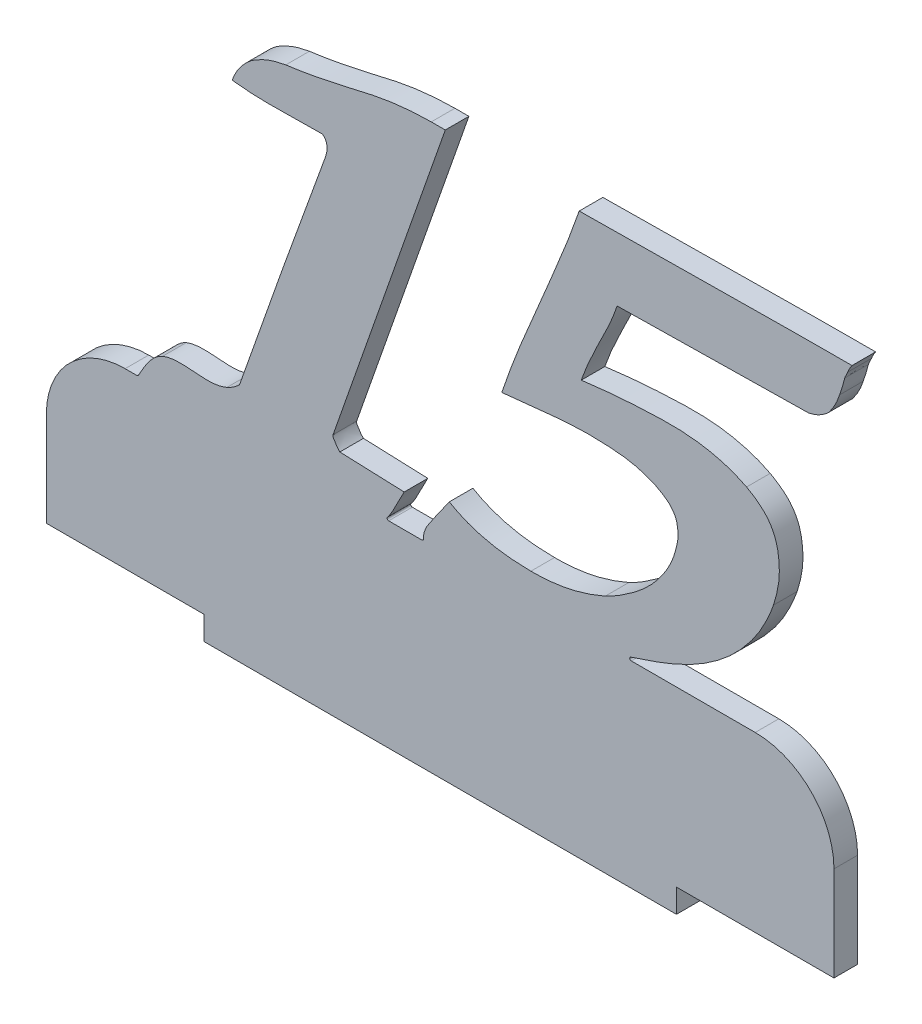
SolidWorks part; units mm, degrees
ref_plane "Front Plane" through (0, 0, 0) normal (0, 0, 1) x (1, 0, 0)
ref_plane "Top Plane" through (0, 0, 0) normal (0, 1, 0) x (1, 0, 0)
ref_plane "Right Plane" through (0, 0, 0) normal (1, 0, 0) x (0, 0, -1)
sketch "Sketch1" plane through (0, 0, 0) normal (0, 0, 1) x (1, 0, 0)
  line L0 (0, 20) -> (100, 20) construction
  line L1 (42.9468, 22) -> (47.8982, 22)
  line L2 (0, 22) -> (0, 0)
  line L3 (0, 0) -> (20, 0)
  line L4 (100, 22) -> (100, 0)
  line L5 (0, 22) -> (11.6163, 22)
  line L6 (90.1102, 22) -> (100, 22)
  line L7 (50.6494, 68.5735) -> (36.3999, 27.9363)
  line L8 (37.26, 26.4703) -> (45.4304, 26.1575)
  line L9 (96.8182, 60.5203) -> (72.4633, 60.1294)
  line L10 (72.918, 22) -> (90.1102, 22)
  line L11 (80, 0) -> (100, 0)
  line L13 (20, 0) -> (20, -3)
  line L14 (20, -3) -> (80, -3)
  line L15 (80, 0) -> (80, -3)
  spline S0 degree 3 poles (45.4304, 26.1575) (44.8355, 25.1443) (44.2903, 23.8221) (43.4345, 22.4246) (43.0957, 22.1163) (42.9468, 22) knots 0 0 0 0 0.504343 0.619768 0.70089 0.70089 0.70089 0.70089
  spline S1 degree 3 poles (11.6163, 22) (11.6951, 22.1343) (12.0206, 22.7022) (12.8266, 24.148) (13.8212, 25.3176) (14.7619, 25.7471) knots 0.170915 0.170915 0.170915 0.170915 0.248912 0.498933 1 1 1 1
  spline S2 degree 3 poles (14.7619, 25.7471) (16.1033, 26.2663) (18.8541, 25.9916) (21.6234, 25.8359) (22.9324, 26.4116) knots 0 0 0 0 0.501452 1 1 1 1
  spline S3 degree 2 poles (22.9324, 26.4116) (23.8139, 26.8022) (24.5157, 27.4672) knots 0 0 0 1 1 1
  spline S4 degree 3 poles (24.5157, 27.4672) (26.298, 32.5023) (29.823, 42.6251) (33.512, 52.6893) (35.3444, 57.7447) knots 0 0 0 0 0.498323 1 1 1 1
  spline S5 degree 3 poles (35.3444, 57.7447) (35.5276, 58.2423) (35.8228, 59.2088) (35.3702, 60.1202) (35.0121, 60.3249) knots 0 0 0 0 0.581397 1 1 1 1
  spline S6 degree 3 poles (35.0121, 60.3249) (33.0954, 60.3587) (29.2904, 60.1747) (25.4774, 60.2795) (23.597, 60.5203) knots 0 0 0 0 0.503015 1 1 1 1
  spline S7 degree 3 poles (23.597, 60.5203) (23.8289, 61.1875) (24.3132, 62.1365) (25.2312, 63.1972) (26.0045, 63.9197) (26.9524, 64.4734) (28.3794, 65.1561) (29.5715, 65.4709) (30.3992, 65.6024) knots 0 0 0 0 0.237267 0.352024 0.469659 0.590381 0.718477 1 1 1 1
  spline S8 degree 3 poles (30.3992, 65.6024) (33.5114, 66.0009) (37.3732, 66.8529) (41.995, 67.9327) (45.0749, 68.4152) (47.368, 68.5627) (48.8706, 68.5735) knots 0 0 0 0 0.501478 0.63281 0.759518 1 1 1 1
  spline S9 degree 3 poles (48.8706, 68.5735) (49.0791, 68.5735) (49.672, 68.5735) (50.2649, 68.5735) (50.6494, 68.5735) knots 0 0 0 0 0.351648 1 1 1 1
  spline S10 degree 3 poles (36.3999, 27.9363) (36.3468, 27.7365) (36.6784, 27.2268) (36.9561, 26.744) (37.26, 26.4703) knots 0 0 0 0 0.324502 1 1 1 1
  spline S11 degree 3 poles (92.3225, 37.1622) (91.7702, 35.6174) (90.7111, 33.3753) (88.7121, 30.7794) (87.021, 28.9699) (85.055, 27.3556) (82.8489, 25.8992) (80.3954, 24.6298) (77.7404, 23.5732) (75.2282, 22.704) (73.61, 22.2029) (72.918, 22) knots 0 0 0 0 0.120139 0.179294 0.238928 0.300824 0.364759 0.431861 0.502352 0.573447 0.626158 0.626158 0.626158 0.626158
  spline S13 degree 3 poles (47.8982, 22) (47.8835, 22.0952) (47.8462, 22.531) (48.0455, 23.3897) (48.6726, 24.4281) (49.4107, 25.443) (50.2199, 26.6356) (50.8129, 27.436) (51.1576, 27.9363) knots 0.184196 0.184196 0.184196 0.184196 0.218197 0.338419 0.488512 0.646372 0.784334 1 1 1 1
  spline S14 degree 3 poles (51.1576, 27.9363) (52.6052, 27.078) (56.0017, 25.802) (59.6114, 25.5069) (61.5172, 25.493) knots 0 0 0 0 0.467741 1 1 1 1
  spline S15 degree 3 poles (61.5172, 25.493) (63.1623, 25.4871) (66.4106, 25.7864) (69.5024, 26.8225) (70.9582, 27.4672) knots 0 0 0 0 0.508189 1 1 1 1
  spline S16 degree 3 poles (70.9582, 27.4672) (72.0392, 27.9891) (73.536, 28.8995) (75.3584, 30.2697) (76.5248, 31.3356) (77.5359, 32.4651) (78.6768, 34.0202) (79.3539, 35.2878) (79.6564, 36.1849) knots 0 0 0 0 0.285167 0.415664 0.541808 0.660346 0.775658 1 1 1 1
  spline S17 degree 3 poles (79.6564, 36.1849) (79.8495, 36.8136) (80.1343, 37.7234) (80.2311, 38.9298) (80.1396, 39.7105) (79.9861, 40.4244) (79.6496, 41.0468) (79.2204, 41.6046) (78.458, 42.2297) (77.3416, 42.8849) (75.8153, 43.4561) (74.1145, 43.904) (71.5713, 44.1672) (68.2052, 44.2958) (64.8201, 44.0361) (62.2151, 43.7366) (60.1238, 43.5188) (58.6885, 43.395) (57.8229, 43.2998) knots 0 0 0 0 0.071404 0.102518 0.130176 0.156356 0.180967 0.206089 0.232106 0.287157 0.345457 0.408083 0.477037 0.621747 0.772341 0.844017 0.905722 1 1 1 1
  spline S18 degree 3 poles (57.8229, 43.2998) (59.2314, 47.5145) (62.6881, 55.7326) (66.2091, 63.9226) (67.6548, 68.163) knots 0 0 0 0 0.497975 1 1 1 1
  spline S19 degree 3 poles (67.6548, 68.163) (73.4145, 68.2313) (84.9599, 68.3492) (96.5051, 68.5053) (102.2913, 68.4953) knots 0 0 0 0 0.498878 1 1 1 1
  spline S20 degree 2 poles (102.2913, 68.4953) (101.9657, 68.04) (101.7635, 67.518) knots 0 0 0 1 1 1
  spline S21 degree 3 poles (101.7635, 67.518) (101.6455, 67.2826) (101.5318, 67.0094) (101.369, 66.7207) (101.3726, 66.6579) knots 0 0 0 0 0.803037 1 1 1 1
  spline S22 degree 3 poles (101.3726, 66.6579) (101.2327, 66.1917) (101.0631, 65.4462) (100.8085, 64.7259) (100.708, 64.4687) knots 0 0 0 0 0.638073 1 1 1 1
  spline S23 degree 2 poles (100.708, 64.4687) (100.2746, 63.0654) (99.3788, 61.9081) knots 0 0 0 1 1 1
  spline S24 degree 2 poles (99.3788, 61.9081) (98.3081, 60.8421) (96.8182, 60.5203) knots 0 0 0 1 1 1
  spline S25 degree 3 poles (72.4633, 60.1294) (71.8819, 58.2941) (70.1425, 54.9138) (68.517, 51.479) (67.9089, 49.6916) knots 0 0 0 0 0.504223 1 1 1 1
  spline S26 degree 3 poles (67.9089, 49.6916) (69.5903, 49.9226) (72.1894, 50.1796) (75.7647, 50.4109) (78.6126, 50.5179) (81.4542, 50.4779) (84.9569, 49.9879) (87.4256, 49.2246) (88.9019, 48.4406) knots 0 0 0 0 0.238617 0.367155 0.503751 0.639403 0.766128 1 1 1 1
  spline S27 degree 3 poles (88.9019, 48.4406) (89.8888, 47.8925) (91.2987, 46.9181) (92.4454, 45.039) (92.8974, 43.5366) (93.0778, 41.9701) (93.0639, 39.8073) (92.6588, 38.2074) (92.3225, 37.1622) knots 0 0 0 0 0.263831 0.382077 0.502054 0.62342 0.745364 1 1 1 1
  dimension "D1" = 100
  dimension "D2" = 3
  dimension "D3" = 20
  dimension "D4" = 20
  dimension "D5" = 20
extrude "Boss-Extrude1" add sketch "Sketch1" along normal blind 3
fillet "Fillet1" radius 10 2 edges at (0, 22, 1.5) (100, 22, 1.5)
fillet "Fillet2" radius 0.2 4 edges at (72.918, 22, 1.5) (42.9468, 22, 1.5) (47.8982, 22, 1.5) (11.6163, 22, 1.5)
